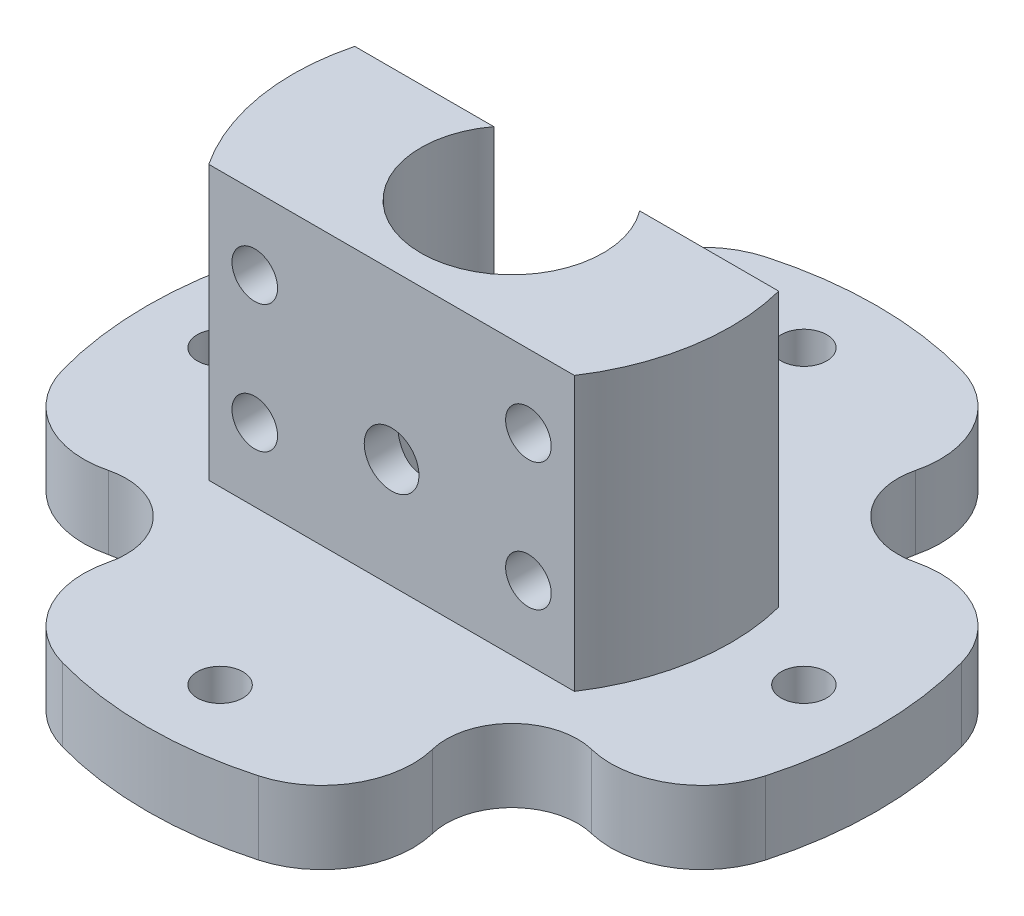
SolidWorks part; units mm, degrees
material "6061 合金"
ref_plane "前视基准面" through (0, 0, 0) normal (0, 0, 1) x (1, 0, 0)
ref_plane "上视基准面" through (0, 0, 0) normal (0, 1, 0) x (1, 0, 0)
ref_plane "右视基准面" through (0, 0, 0) normal (1, 0, 0) x (0, 0, -1)
other "Configuration Table"
sketch "草图1" plane through (0, 0, 0) normal (0, 1, 0) x (1, 0, 0)
  line L0 (-11.619, 3) -> (11.619, 3)
  line L1 (-10.022, -6.6) -> (10.022, -6.6)
  line L2 (0, 25.9007) -> (0, -26.4323) construction
  line L3 (0, 0) -> (16, 0) construction
  line L4 (-12.3744, 12.3744) -> (0, 0) construction
  circle A0 centre (0, 0) radius 5
  circle A1 centre (0, 0) radius 12
  circle A2 centre (0, 0) radius 20
  circle A3 centre (0, 0) radius 16 construction
  circle A4 centre (16, 0) radius 1.25
  circle A5 centre (0, -16) radius 1.25
  circle A6 centre (-16, 0) radius 1.25
  circle A7 centre (0, 16) radius 1.25
  circle A8 centre (0, 16) radius 3 construction
  circle A9 centre (0, 0) radius 17.5 construction
  circle A10 centre (-12.3744, 12.3744) radius 3.6
  circle A11 centre (12.3744, 12.3744) radius 3.6
  circle A12 centre (12.3744, -12.3744) radius 3.6
  circle A13 centre (-12.3744, -12.3744) radius 3.6
  circle A14 centre (16, 0) radius 3 construction
  circle A15 centre (0, -16) radius 3 construction
  circle A16 centre (-16, 0) radius 3 construction
  point P23 (0, 0)
  point P34 (0, 0)
  point P41 (0, 0)
  dimension "D1" = 10
  dimension "D2" = 24
  dimension "D3" = 40
  dimension "D4" = 32
  dimension "D7" = 2.5
  dimension "D9" = 6
  dimension "D11" = 35
  dimension "D12" = 7.2
  dimension "D5" = 3
  dimension "D6" = 6.6
  dimension "D8" = 90
  dimension "D10" = 4
  dimension "D15" = 45
  dimension "D14" = 4
  dimension "D13" = 4
sketch "草图2" plane through (0, 0, 0) normal (0, 1, 0) x (1, 0, 0)
  line L0 (-10.022, -6.6) -> (10.022, -6.6) construction
  line L1 (-10.022, -6.6) -> (10.022, -6.6)
  line L2 (-11.619, 3) -> (11.619, 3) construction
  line L3 (-11.619, 3) -> (-4, 3)
  line L4 (4, 3) -> (11.619, 3)
  circle A0 centre (0, 0) radius 5 construction
  circle A1 centre (0, 0) radius 12 construction
  arc A2 (-4, 3) -> (4, 3) centre (0, 0) ccw
  arc A3 (-11.619, 3) -> (-10.022, -6.6) centre (0, 0) ccw
  arc A4 (10.022, -6.6) -> (11.619, 3) centre (0, 0) ccw
extrude "凸台-拉伸1" add sketch "草图2" along normal blind 15
sketch "草图3" plane through (0, 0, 0) normal (0, 1, 0) x (1, 0, 0)
  circle A0 centre (0, -16) radius 1.25 construction
  circle A1 centre (16, 0) radius 1.25 construction
  circle A2 centre (-16, 0) radius 1.25 construction
  circle A3 centre (0, 16) radius 1.25 construction
  circle A4 centre (0, 0) radius 5 construction
  circle A5 centre (0, 0) radius 20 construction
  circle A6 centre (0, -16) radius 1.25
  circle A7 centre (16, 0) radius 1.25
  circle A8 centre (-16, 0) radius 1.25
  circle A9 centre (0, 16) radius 1.25
  circle A10 centre (0, 0) radius 5
  circle A11 centre (0, 0) radius 20
  point P18 (0, 0)
extrude "凸台-拉伸2" add sketch "草图3" against normal blind 4
cosmetic thread "装饰螺纹线1"
cosmetic thread "装饰螺纹线2"
cosmetic thread "装饰螺纹线3"
cosmetic thread "装饰螺纹线4"
sketch "草图4" plane through (0, 0, 0) normal (0, 1, 0) x (1, 0, 0)
  circle A0 centre (12.3744, -12.3744) radius 3.6 construction
  circle A1 centre (12.3744, 12.3744) radius 3.6 construction
  circle A2 centre (-12.3744, 12.3744) radius 3.6 construction
  circle A3 centre (-12.3744, -12.3744) radius 3.6 construction
  circle A4 centre (12.3744, -12.3744) radius 3.6
  circle A5 centre (12.3744, 12.3744) radius 3.6
  circle A6 centre (-12.3744, 12.3744) radius 3.6
  circle A7 centre (-12.3744, -12.3744) radius 3.6
extrude "切除-拉伸1" cut sketch "草图4" against normal through all
fillet "圆角1" radius 5 8 edges at (15.96, -2, 12.0531) (12.0531, -2, 15.96) (-12.0531, -2, 15.96) (-15.96, -2, 12.0531) (-15.96, -2, -12.0531) (-12.0531, -2, -15.96) (12.0531, -2, -15.96) (15.96, -2, -12.0531)
sketch "草图5" plane through (0, 0, -3) normal (0, 0, -1) x (-1, 0, 0)
  line L0 (-11.619, 15) -> (-4, 15) construction
  line L1 (7.5, 11) -> (-7.5, 11) construction
  line L2 (7.5, 11) -> (7.5, 4) construction
  line L3 (7.5, 4) -> (-7.5, 4) construction
  line L4 (-7.5, 11) -> (-7.5, 4) construction
  line L5 (7.5, 11) -> (-7.5, 4) construction
  line L6 (7.5, 4) -> (-7.5, 11) construction
  circle A0 centre (-7.5, 11) radius 1.25
  circle A1 centre (-7.5, 4) radius 1.25
  circle A2 centre (7.5, 11) radius 1.25
  circle A3 centre (7.5, 4) radius 1.25
  circle A4 centre (0, 6) radius 1.5
  point P0 (0, 7.5)
  dimension "D4" = 2.5
  dimension "D5" = 3
  dimension "D6" = 2
  dimension "D1" = 4
  dimension "D2" = 7
  dimension "D3" = 15
extrude "切除-拉伸2" cut sketch "草图5" against normal through all
cosmetic thread "装饰螺纹线5"
cosmetic thread "装饰螺纹线6"
cosmetic thread "装饰螺纹线7"
cosmetic thread "装饰螺纹线8"
sketch "草图8" plane through (0, -4, 0) normal (0, -1, 0) x (1, 0, 0)
  circle A0 centre (0, 0) radius 5
